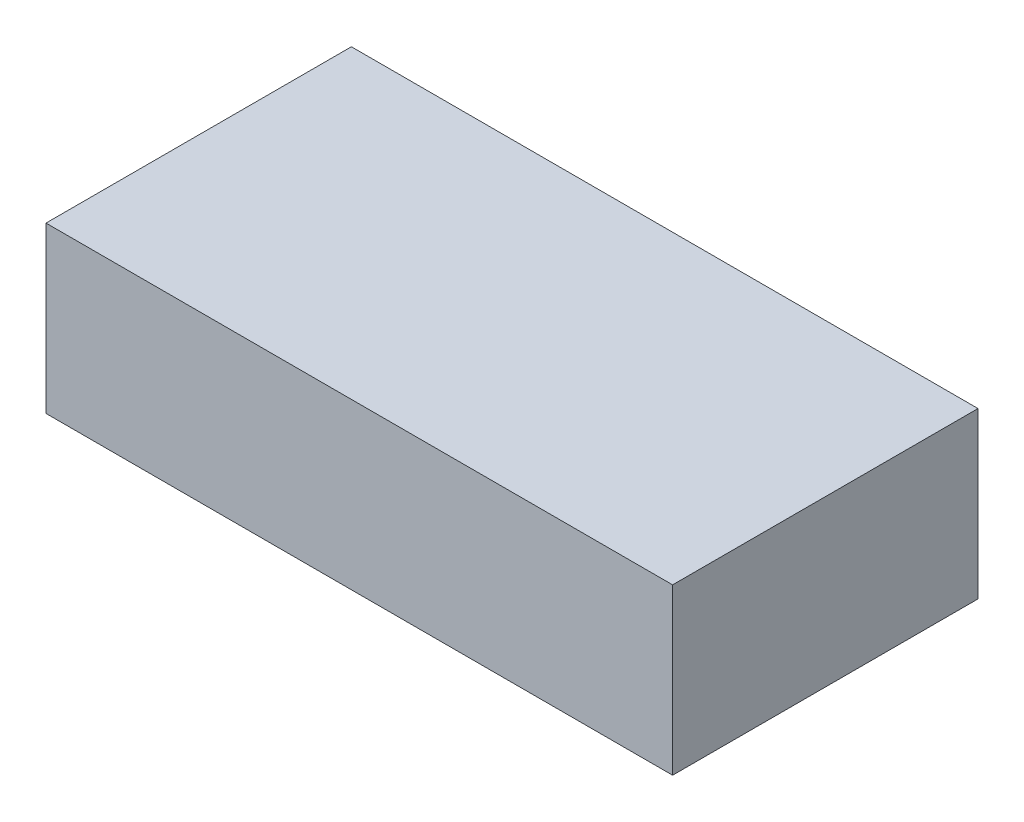
SolidWorks part; units mm, degrees
ref_plane "Front Plane" through (0, 0, 0) normal (0, 0, 1) x (1, 0, 0)
ref_plane "Top Plane" through (0, 0, 0) normal (0, 1, 0) x (1, 0, 0)
ref_plane "Right Plane" through (0, 0, 0) normal (1, 0, 0) x (0, 0, -1)
sketch "Sketch1" plane through (0, 0, 0) normal (0, 1, 0) x (1, 0, 0)
  line L1 (0, 0) -> (241.3, 0)
  line L2 (0, 0) -> (0, 117.602)
  line L3 (0, 117.602) -> (241.3, 117.602)
  line L4 (241.3, 0) -> (241.3, 117.602)
  dimension "D1" = 241.3
  dimension "D2" = 117.602
extrude "Boss-Extrude1" add sketch "Sketch1" along normal blind 63.5
